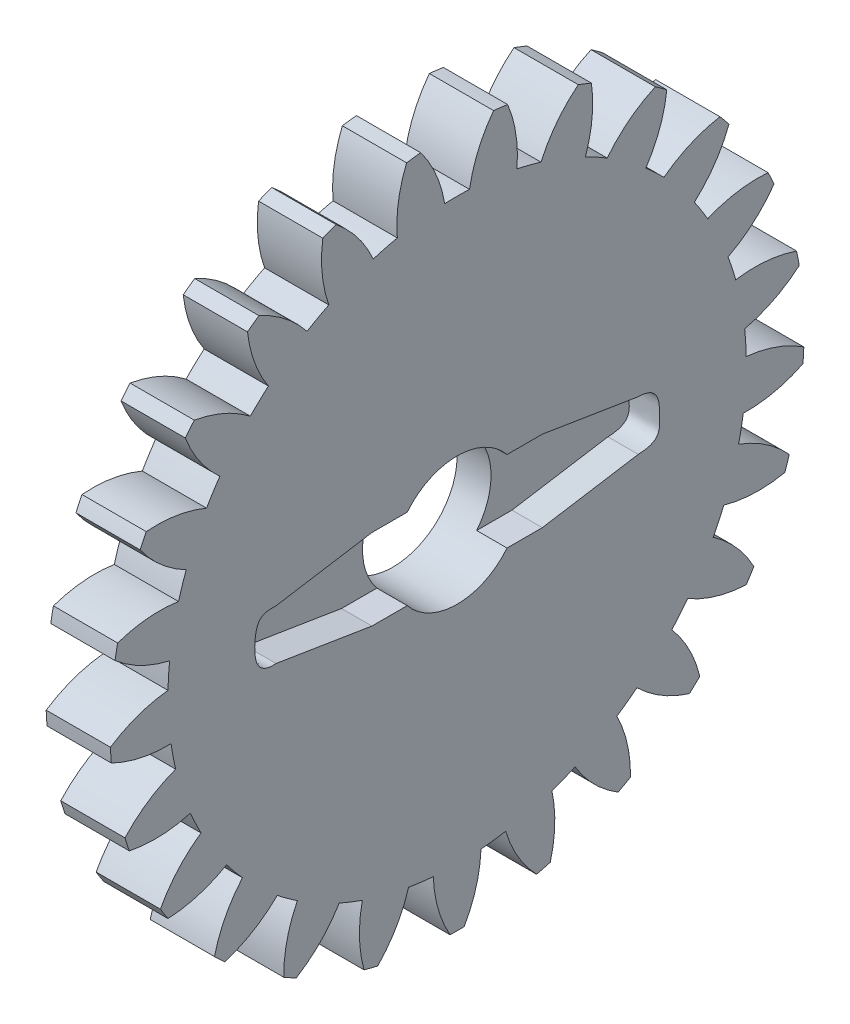
SolidWorks part; units mm, degrees
ref_plane "Plane1" through (0, 0, 0) normal (0, 0, 1) x (1, 0, 0)
ref_plane "Plane2" through (0, 0, 0) normal (0, 1, 0) x (1, 0, 0)
ref_plane "Plane3" through (0, 0, 0) normal (1, 0, 0) x (0, 0, -1)
other "Configuration Table"
sketch "HoldingSke" plane through (0, 0, 0) normal (0, 1, 0) x (1, 0, 0)
  line L0 (0, 0) -> (230.2022, -107.345)
  line L1 (-15, 0) -> (100, 0) construction
  line L2 (0, 0) -> (-2.1039, 2.3779)
  line L3 (0, 0) -> (-11.863, 4.5341)
  line L4 (0, 0) -> (7.8269, 3.6497)
  line L5 (0, 0) -> (-47.5972, -17.7524)
  line L6 (0, 0) -> (-5.2639, -3.5516)
  line L7 (-2.1039, 2.3779) -> (8.8308, 51.9871)
  line L8 (-76.2, 54.61) -> (-61.976, 54.61)
  line L9 (-71.009, 38.7566) -> (-53.1078, 45.2721)
  line L10 (-76.2, 71.12) -> (104.1128, 71.12)
  line L11 (0, 0) -> (-6.35, 0)
  line L12 (-76.2, 101.6) -> (-76.0984, 101.6)
  line L13 (24.9733, 27.94) -> (52.9518, 28.4284)
  line L14 (24.9733, 27.94) -> (24.9746, 27.94)
  line L15 (24.9733, 27.94) -> (100.4006, 29.5858)
  circle A0 centre (0, 0) radius 6.35
  circle A1 centre (0, 0) radius 28.5737
  circle A2 centre (0, 0) radius 38.1
  circle A3 centre (0, 0) radius 6.35
  dimension "MHD" = 57.1475
  dimension "Hub_dia" = 76.2
  dimension "Bore" = 12.7
  dimension "MBD" = 12.7
  dimension "Num_teeth" = 25
  dimension "Pitch" = 254
  dimension "Overall_len" = 50.8
  dimension "Show_teeth" = 25
  dimension "Thickness" = 6.35
  dimension "OAL" = 50.8001
  dimension "T_dim" = 14.224
  dimension "Ap" = 20
  dimension "H" = 19.05
  dimension "Pitch_radius" = 180.3128
  dimension "Width" = 6.35
  dimension "Backlash" = 0.1016
  dimension "Addendum_fac" = 1
  dimension "Dedendum_fac" = 1.25
  dimension "Clearance_fac" = 0.25
  dimension "Dedendum_add" = 0.0013
sketch "BasProSke" plane through (0, 0, 0) normal (0, 1, 0) x (1, 0, 0)
  line L0 (-10, 0) -> (60, 0) construction
  line L1 (0, 0) -> (0, 34.29)
  line L2 (0, 0) -> (6.35, 0)
  line L3 (6.35, 0) -> (6.35, 34.29)
  line L4 (6.35, 34.29) -> (0, 34.29)
  dimension "Thickness" = 6.35
  dimension "Diameter" = 68.58
revolve "Base-Revolve" add sketch "BasProSke" angle 360 about L0
sketch "TooCutSke" plane through (0, 0, 0) normal (1, 0, 0) x (0, 0, -1)
  line L1 (0, 0) -> (0, 107) construction
  line L2 (0, 0) -> (-2.1713, 31.6757) construction
  line L3 (0, 0) -> (-7.9456, 62.8962) construction
  line L4 (-2.1713, 31.6757) -> (-3.9728, 31.4481) construction
  arc A0 (1.2276, 28.5473) -> (-1.2276, 28.5473) centre (0, 0) ccw
  arc A1 (3.6197, 34.124) -> (-3.6197, 34.124) centre (0, 0) ccw
  circle A2 centre (0, 0) radius 31.75 construction
  circle A3 centre (0, 0) radius 29.8352 construction
  arc A4 (-1.2276, 28.5473) -> (-3.6197, 34.124) centre (-13.7573, 26.4741) ccw
  arc A5 (3.6197, 34.124) -> (1.2276, 28.5473) centre (13.7573, 26.4741) ccw
  dimension "Root_dia" = 57.1475
  dimension "Overcut_dia" = 68.6308
  dimension "Pitch_dia" = 63.5
  dimension "Base_dia" = 59.6705
  dimension "Flank_rad" = 12.7
  dimension "Half_ang" = 7.2
  dimension "Half_CT" = 1.8158
extrude "ToothCut" cut sketch "TooCutSke" along normal through all
fillet "Breaks" [suppressed] radius 0.0508
fillet "RootFillets" [suppressed] radius 0.6363
pattern_circular "TeethCuts" count 25 every 14.4 about axis through (-10, 0, 0) along (1, 0, 0) of "ToothCut", "RootFillets", "Breaks"
sketch "HubNeaOneSke" plane through (0, 0, 0) normal (-1, 0, 0) x (0, 0, 1)
  circle A0 centre (0, 0) radius 28.5737
  dimension "Diameter" = 57.1475
extrude "HubNearOne" [suppressed] add sketch "HubNeaOneSke" along normal blind 44.4501
sketch "HubNeaBotSke" plane through (0, 0, 0) normal (-1, 0, 0) x (0, 0, 1)
  circle A0 centre (0, 0) radius 28.5737
  dimension "Diameter" = 57.1475
extrude "HubNearBoth" [suppressed] add sketch "HubNeaBotSke" along normal blind 22.225
ref_plane "FarPln" through (6.35, 0, 0) normal (1, 0, 0) x (0, 0, -1)
sketch "HubFarSke" plane through (6.35, 0, 0) normal (1, 0, 0) x (0, 0, -1)
  circle A0 centre (0, 0) radius 28.5737
  dimension "Diameter" = 57.1475
extrude "HubFar" [suppressed] add sketch "HubFarSke" along normal blind 22.225
sketch "BorSke" plane through (0, 0, 0) normal (1, 0, 0) x (0, 0, -1)
  circle A0 centre (0, 0) radius 6.35
  dimension "Diameter" = 12.7
extrude "Bore" cut sketch "BorSke" along normal mid plane 101.6001
sketch "KeySke" plane through (0, 0, 0) normal (1, 0, 0) x (0, 0, -1)
  line L0 (-1.5875, 0) -> (-1.5875, 7.874)
  line L1 (-1.5875, 7.874) -> (1.5875, 7.874)
  line L2 (1.5875, 7.874) -> (1.5875, 0)
  line L3 (0, 0) -> (0, 34) construction
  line L4 (-1.5875, 0) -> (1.5875, 0)
  dimension "Offset" = 7.874
  dimension "Width" = 3.175
extrude "Keyway" [suppressed] cut sketch "KeySke" along normal mid plane 101.6001
pattern_circular "Keyway2" [suppressed] count 2 every 90 about axis through (-10, 0, 0) along (1, 0, 0)
sketch "Sketch1" plane through (6.35, 0, 0) normal (1, 0, 0) x (0, 0, -1)
  line L0 (17.8989, -2.468) -> (8.4192, -4)
  line L1 (8.4192, -4) -> (3.9192, -4)
  arc A0 (17.8989, -2.468) -> (17.8989, 2.468) centre (17.5, 0) ccw construction
  arc A1 (3.9192, 4) -> (-3.9192, 4) centre (0, 0) ccw construction
  arc A2 (-3.9192, -4) -> (3.9192, -4) centre (0, 0) ccw construction
  arc A3 (-17.8989, 2.468) -> (-17.8989, -2.468) centre (-17.5, 0) ccw construction
  spline S0 degree 1 poles (8.4192, 4) (17.8989, 2.468) knots 0 0 1 1
  spline S1 degree 3 poles (17.8989, 2.468) (19.5695, 2.4446) (20.0254, 1.3257) (19.9796, -1.038) (20.1865, -2.4001) (17.8989, -2.468) knots 0 0 0 0 0.495063 0.595063 1 1 1 1
  spline S2 degree 1 poles (8.4192, 4) (3.9192, 4) knots 0 0 1 1
  spline S3 degree 2 poles (3.9192, 4) (0, 7.2) (-3.9192, 4) knots 0 0 0 1 1 1
  spline S4 degree 1 poles (-3.9192, 4) (-8.4192, 4) knots 0 0 1 1
  spline S5 degree 2 poles (3.9192, -4) (0, -7.2) (-3.9192, -4) knots 0 0 0 1 1 1
  spline S6 degree 1 poles (-3.9192, -4) (-8.4192, -4) knots 0 0 1 1
  spline S7 degree 1 poles (-8.4192, 4) (-17.8989, 2.468) knots 0 0 1 1
  spline S8 degree 1 poles (-8.4192, -4) (-17.8989, -2.468) knots 0 0 1 1
  spline S9 degree 3 poles (-17.8989, 2.468) (-19.1496, 2.5093) (-19.8734, 2.372) (-20.0787, -1.2087) (-19.5434, -2.6068) (-17.8989, -2.468) knots 0 0 0 0 0.571712 0.671712 1 1 1 1
extrude "Cut-Extrude1" cut sketch "Sketch1" against normal blind 3
equation "' \"Pitch@HoldingSke\" = 4"
equation "' \"Num_teeth@HoldingSke\" = 12"
equation "' \"Ap@HoldingSke\" =  20"
equation "' \"Ap@HoldingSke\" = 20"
equation "' \"Width@HoldingSke\" = 0.5"
equation "' \"Hub_dia@HoldingSke\"= 1"
equation "' \"Hub_dia@HoldingSke\" = 1"
equation "' \"Overall_len@HoldingSke\" = 1.0"
equation "' \"Bore@HoldingSke\" = 0.75"
equation "' \"T_dim@HoldingSke\" = 0.85"
equation "' \"Width@KeySke\" = 0.25"
equation "' \"Show_teeth@HoldingSke\" = 13"
equation "' \"Backlash@HoldingSke\" = 0.009"
equation "' \"Addendum_fac@HoldingSke\" = 1.0"
equation "' \"Dedendum_fac@HoldingSke\" = 1.25"
equation "' \"Dedendum_add@HoldingSke\" = 0.00005"
equation "' \"Clearance_fac@HoldingSke\" = 0.25"
equation "' \"Pitch@HoldingSke\" = 0.5"
equation "' \"Num_teeth@HoldingSke\" = 23"
equation "' \"Show_teeth@HoldingSke\" = 23"
equation "' \"Backlash@HoldingSke\" = 0.0375"
equation "\"Overcut_dia@TooCutSke\" = (\"Num_teeth@HoldingSke\" + 2 * \"Addendum_fac@HoldingSke\") / \"Pitch@HoldingSke\" + 0.002"
equation "\"Pitch_dia@TooCutSke\" = \"Num_teeth@HoldingSke\" / \"Pitch@HoldingSke\""
equation "\"Base_dia@TooCutSke\" = \"Num_teeth@HoldingSke\" / \"Pitch@HoldingSke\" * cos((\"Ap@HoldingSke\"  * 3.14159265 / 180))"
equation "\"Root_dia@TooCutSke\" = (\"Num_teeth@HoldingSke\" + 2) / \"Pitch@HoldingSke\" - 2 * (\"Addendum_fac@HoldingSke\" + \"Dedendum_fac@HoldingSke\") / \"Pitch@HoldingSke\" - \"Dedendum_add@HoldingSke\" * 2"
equation "\"Half_ang@TooCutSke\" = 180 / \"Num_teeth@HoldingSke\""
equation "\"Half_CT@TooCutSke\" = \"Num_teeth@HoldingSke\" / \"Pitch@HoldingSke\" * sin((3.14159265 / 2 / \"Num_teeth@HoldingSke\")) / 2 - 7 * \"Backlash@HoldingSke\" / 4"
equation "\"Flank_rad@TooCutSke\" = \"Num_teeth@HoldingSke\" / \"Pitch@HoldingSke\" / 5"
equation "\"Radius@RootFillets\" = \"Clearance_fac@HoldingSke\" / \"Pitch@HoldingSke\" + \"Dedendum_add@HoldingSke\""
equation "\"Break_rad@Breaks\" = 0.02 / \"Pitch@HoldingSke\""
equation "\"Thickness@HoldingSke\" = \"Width@HoldingSke\""
equation "\"OAL@HoldingSke\" = \"Thickness@HoldingSke\""
equation "\"MHD@HoldingSke\" = (\"Num_teeth@HoldingSke\" + 2) / \"Pitch@HoldingSke\" - 2 * (\"Addendum_fac@HoldingSke\" + \"Dedendum_fac@HoldingSke\")  / \"Pitch@HoldingSke\" - \"Dedendum_add@HoldingSke\" * 2"
equation "\"MBD@HoldingSke\" = (\"Num_teeth@HoldingSke\" + 2) / \"Pitch@HoldingSke\" - 2 * (\"Addendum_fac@HoldingSke\" + \"Dedendum_fac@HoldingSke\")  / \"Pitch@HoldingSke\" - \"Dedendum_add@HoldingSke\" * 2 - 0.002"
equation "\"MHD@HoldingSke\" = ((sgn( \"MHD@HoldingSke\" - \"Hub_dia@HoldingSke\" )-1)*( \"MHD@HoldingSke\" - \"Hub_dia@HoldingSke\" ))/-2+ \"Hub_dia@HoldingSke\""
equation "\"MBD@HoldingSke\" = ((sgn( \"MBD@HoldingSke\" - \"Bore@HoldingSke\" )-1)*( \"MBD@HoldingSke\" - \"Bore@HoldingSke\" ))/-2+ \"Bore@HoldingSke\""
equation "\"OAL@HoldingSke\" = ((sgn( \"OAL@HoldingSke\" - \"Overall_len@HoldingSke\" )+1)*( \"OAL@HoldingSke\" - \"Overall_len@HoldingSke\" ))/2 + \"Overall_len@HoldingSke\" + 0.000002"
equation "\"Num_teeth@TeethCuts\" = int( \"Show_teeth@HoldingSke\" ) + 1"
equation "\"Num_teeth@TeethCuts\" = ((sgn( \"Num_teeth@TeethCuts\" - \"Num_teeth@HoldingSke\" )-1)*( \"Num_teeth@TeethCuts\" - \"Num_teeth@HoldingSke\" ))/-2+ \"Num_teeth@HoldingSke\""
equation "\"Num_teeth@TeethCuts\" = ((sgn( \"Num_teeth@TeethCuts\" - 2.0)+1)*( \"Num_teeth@TeethCuts\" - 2.0))/2 +2.0"
equation "\"Angle@TeethCuts\" = 360.0 / \"Num_teeth@HoldingSke\""
equation "\"Diameter@BasProSke\" = (\"Num_teeth@HoldingSke\" + 2 * \"Addendum_fac@HoldingSke\") / \"Pitch@HoldingSke\""
equation "\"Thickness@BasProSke\"  = \"Thickness@HoldingSke\""
equation "' \"Fillet_rad@BasProSke\" =  \"Thickness@HoldingSke\" * 0.05"
equation "' \"Fillet_rad@BasProSke\" = \"Thickness@HoldingSke\" * 0.05"
equation "\"MHD@HoldingSke\" = ((sgn( \"MHD@HoldingSke\" - \"Root_dia@TooCutSke\" )-1)*( \"MHD@HoldingSke\" - \"Root_dia@TooCutSke\" ))/-2+ \"Root_dia@TooCutSke\""
equation "\"Diameter@HubNeaOneSke\" = \"MHD@HoldingSke\""
equation "\"Length@HubNearOne\" = \"OAL@HoldingSke\" - \"Thickness@BasProSke\""
equation "\"Diameter@HubNeaBotSke\" = \"MHD@HoldingSke\""
equation "\"Length@HubNearBoth\" = ( \"OAL@HoldingSke\" - \"Thickness@BasProSke\" ) / 2.0"
equation "\"Thickness@FarPln\" = \"Thickness@BasProSke\""
equation "\"Diameter@HubFarSke\" = \"MHD@HoldingSke\""
equation "\"Length@HubFar\" = ( \"OAL@HoldingSke\" - \"Thickness@BasProSke\" ) / 2.0"
equation "\"Diameter@BorSke\" = \"MBD@HoldingSke\""
equation "\"D1@Bore\" = \"OAL@HoldingSke\" * 2.0"
equation "\"D1@Keyway\" = \"OAL@HoldingSke\" * 2.0"
equation "\"Offset@KeySke\" = \"T_dim@HoldingSke\" - \"MBD@HoldingSke\" / 2.0"
